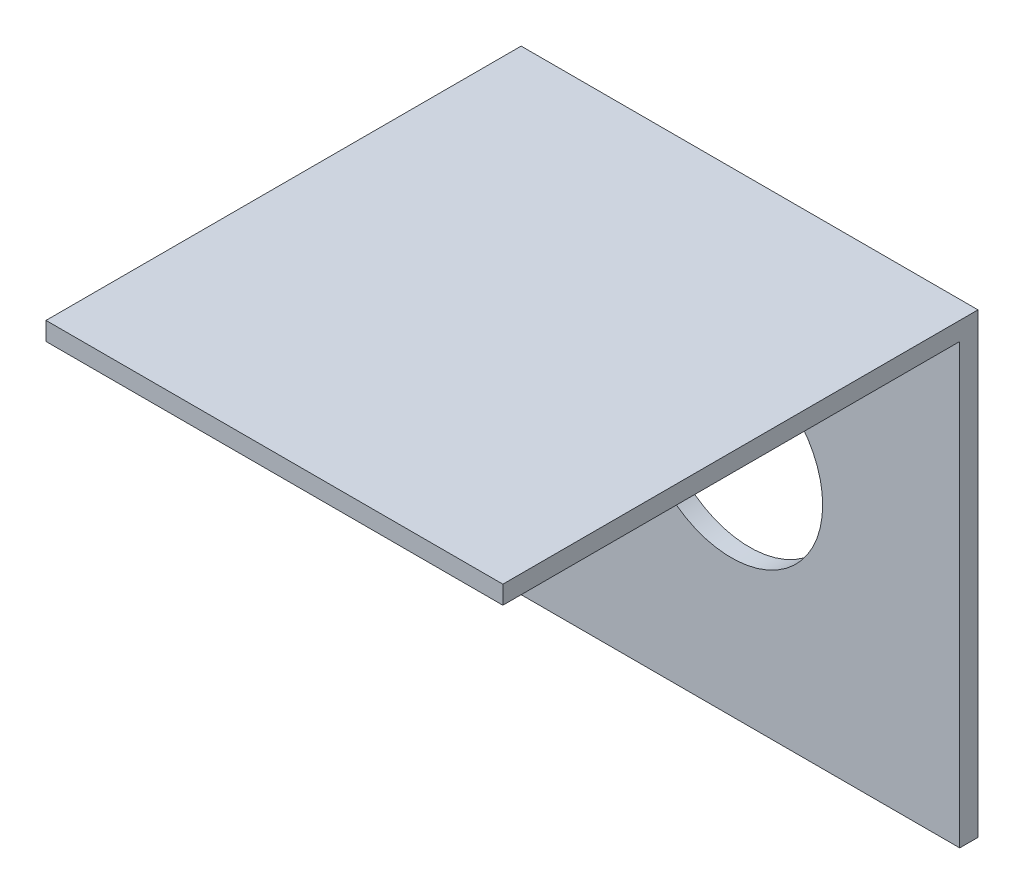
SolidWorks part; units mm, degrees
ref_plane "Front Plane" through (0, 0, 0) normal (0, 0, 1) x (1, 0, 0)
ref_plane "Top Plane" through (0, 0, 0) normal (0, 1, 0) x (1, 0, 0)
ref_plane "Right Plane" through (0, 0, 0) normal (1, 0, 0) x (0, 0, -1)
sketch "Sketch1" plane through (0, 0, 0) normal (0, 0, 1) x (1, 0, 0)
  line L1 (-25, -25) -> (25, -25)
  line L2 (-25, -25) -> (-25, 25)
  line L3 (-25, 25) -> (25, 25)
  line L4 (25, -25) -> (25, 25)
  line L5 (-25, -25) -> (25, 25) construction
  line L6 (-25, 25) -> (25, -25) construction
  point P1 (0, 0)
  dimension "D1" = 50
  dimension "D2" = 50
extrude "Boss-Extrude1" add sketch "Sketch1" along normal blind 2
sketch "Sketch2" plane through (0, 0, 2) normal (0, 0, 1) x (1, 0, 0)
  line L0 (0, 0) -> (0, 25) construction
  line L1 (25, 25) -> (-25, 25) construction
  line L2 (25, -25) -> (25, 25) construction
  line L3 (-25, 25) -> (25, 25)
  line L4 (-25, 25) -> (-25, 23)
  line L5 (-25, 23) -> (25, 23)
  line L6 (25, 25) -> (25, 23)
  dimension "D1" = 2
extrude "Boss-Extrude2" add sketch "Sketch2" along normal blind 50
sketch "Sketch3" plane through (0, 0, 0) normal (0, 0, -1) x (-1, 0, 0)
  circle A0 centre (0, 0) radius 10
extrude "Cut-Extrude2" cut sketch "Sketch3" against normal blind 20
